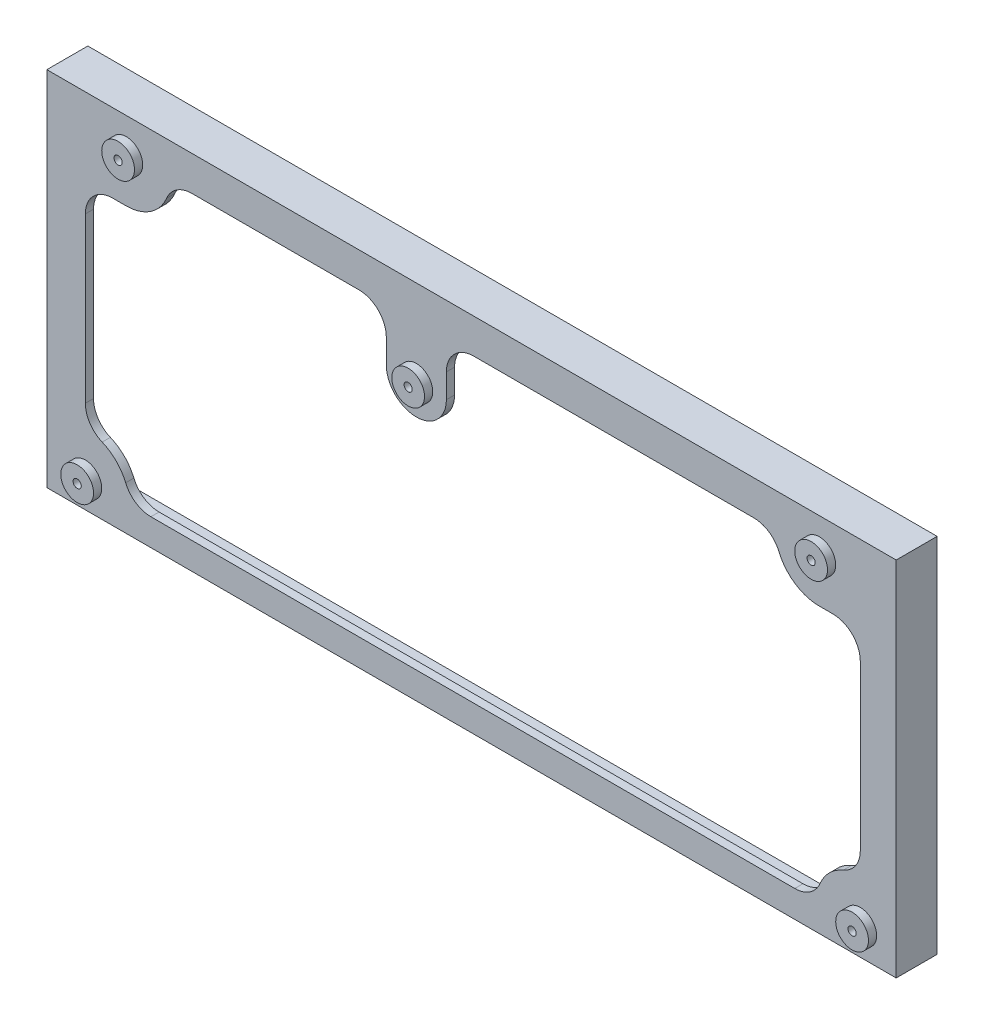
SolidWorks part; units mm, degrees
ref_plane "Front Plane" through (0, 0, 0) normal (0, 0, 1) x (1, 0, 0)
ref_plane "Top Plane" through (0, 0, 0) normal (0, 1, 0) x (1, 0, 0)
ref_plane "Right Plane" through (0, 0, 0) normal (1, 0, 0) x (0, 0, -1)
sketch "Sketch1" plane through (0, 0, 0) normal (0, 0, 1) x (1, 0, 0)
  circle A0 centre (0, 0) radius 1.5
  circle A1 centre (-106.24, 18.83) radius 1.5
  circle A2 centre (147.61, 18.83) radius 1.5
  circle A3 centre (-121.24, -91.25) radius 1.5
  circle A4 centre (162.61, -91.25) radius 1.5
  circle A5 centre (0, 0) radius 6
  circle A6 centre (-106.24, 18.83) radius 6
  circle A7 centre (147.61, 18.83) radius 6
  circle A8 centre (-121.24, -91.25) radius 6
  circle A9 centre (162.61, -91.25) radius 6
  dimension "D1" = 3
  dimension "D4" = 18.83
  dimension "D5" = 162.61
  dimension "D2" = 147.61
  dimension "D3" = 106.24
  dimension "D6" = 121.24
  dimension "D7" = 91.25
  dimension "D8" = 4.5
extrude "Display screw pattern" add sketch "Sketch1" along normal blind 3
sketch "Sketch2" plane through (0, 0, 0) normal (0, 0, -1) x (-1, 0, 0)
  line L0 (135.34, 31.53) -> (135.34, -101.07)
  line L1 (133.84, 30.03) -> (-174.26, 30.03) construction
  line L2 (133.84, 30.03) -> (133.84, -99.57) construction
  line L3 (133.84, -99.57) -> (-174.26, -99.57) construction
  line L4 (-174.26, 30.03) -> (-174.26, -99.57) construction
  line L5 (135.34, -101.07) -> (-175.76, -101.07)
  line L6 (-175.76, 31.53) -> (-175.76, -101.07)
  line L7 (135.34, 31.53) -> (-175.76, 31.53)
  circle A2 centre (106.24, 18.83) radius 4
  circle A3 centre (106.24, 18.83) radius 4
  circle A8 centre (0, 0) radius 4
  circle A9 centre (0, 0) radius 4
  circle A11 centre (121.24, -91.25) radius 4
  circle A12 centre (121.24, -91.25) radius 4
  circle A14 centre (-147.61, 18.83) radius 4
  circle A15 centre (-147.61, 18.83) radius 4
  circle A17 centre (-162.61, -91.25) radius 4
  circle A18 centre (-162.61, -91.25) radius 4
  dimension "D6" = 11.2
  dimension "D7" = 26.65
  dimension "D8" = 8.32
  dimension "D9" = 27.6
  dimension "D1" = 2
  dimension "D2" = 2
  dimension "D3" = 2
  dimension "D4" = 2
  dimension "D5" = 2
  dimension "D10" = 1.5
extrude "Display backplane" add sketch "Sketch2" along normal blind 3
sketch "Sketch3" plane through (0, 0, 0) normal (0, 0, 1) x (1, 0, 0)
  line L1 (162.61, -7.17) -> (162.61, -67.25)
  line L2 (138.61, -91.25) -> (-97.24, -91.25)
  line L3 (-121.24, -67.25) -> (-121.24, -7.17)
  line L5 (-82.24, 18.83) -> (-21, 18.83)
  line L6 (11, 8.83) -> (11, 0)
  line L7 (-11, 0) -> (-11, 8.83)
  line L8 (21, 18.83) -> (123.61, 18.83)
  line L9 (147.61, 2.83) -> (152.61, 2.83)
  line L10 (-106.24, 2.83) -> (-111.24, 2.83)
  arc A0 (123.61, 18.83) -> (132.8408, 12.6762) centre (123.61, 8.83) cw
  arc A1 (152.61, 2.83) -> (162.61, -7.17) centre (152.61, -7.17) cw
  arc A2 (162.61, -67.25) -> (156.4562, -76.4808) centre (152.61, -67.25) cw
  circle A4 centre (-121.24, -91.25) radius 16
  arc A5 (-106.4708, -85.0962) -> (-115.0862, -76.4808) centre (-121.24, -91.25) ccw
  arc A6 (138.61, -91.25) -> (147.8408, -85.0962) centre (138.61, -81.25) ccw
  circle A7 centre (162.61, -91.25) radius 16
  arc A8 (156.4562, -76.4808) -> (147.8408, -85.0962) centre (162.61, -91.25) ccw
  arc A9 (-97.24, -91.25) -> (-106.4708, -85.0962) centre (-97.24, -81.25) cw
  arc A10 (-121.24, -67.25) -> (-115.0862, -76.4808) centre (-111.24, -67.25) ccw
  arc A11 (-111.24, 2.83) -> (-121.24, -7.17) centre (-111.24, -7.17) ccw
  arc A12 (-82.24, 18.83) -> (-91.4708, 12.6762) centre (-82.24, 8.83) ccw
  circle A15 centre (0, 0) radius 11
  arc A16 (-11, 0) -> (11, 0) centre (0, 0) ccw
  arc A29 (21, 18.83) -> (11, 8.83) centre (21, 8.83) ccw
  arc A30 (-11, 8.83) -> (-21, 18.83) centre (-21, 8.83) ccw
  circle A36 centre (-106.24, 18.83) radius 16
  arc A37 (-106.24, 2.83) -> (-91.4708, 12.6762) centre (-106.24, 18.83) ccw
  circle A38 centre (147.61, 18.83) radius 16
  arc A39 (132.8408, 12.6762) -> (147.61, 2.83) centre (147.61, 18.83) ccw
  point P29 (131.61, 18.83)
  point P43 (162.61, -75.25)
  point P47 (146.61, -91.25)
  point P50 (-105.24, -91.25)
  point P53 (-121.24, -75.25)
  point P58 (-90.24, 18.83)
  dimension "D6" = 10
  dimension "D7" = 10
  dimension "D1" = 10
  dimension "D2" = 5
  dimension "D3" = 10
  dimension "D4" = 10
  dimension "D5" = 10
extrude "Backplane weight reduction" cut sketch "Sketch3" against normal through all both and the other way through all
sketch "Sketch4" plane through (0, 0, -3) normal (0, 0, -1) x (-1, 0, 0)
  line L12 (134.34, 30.53) -> (-174.76, 30.53)
  line L13 (-174.76, 30.53) -> (-174.76, -100.07)
  line L14 (-174.76, -100.07) -> (134.34, -100.07)
  line L15 (134.34, -100.07) -> (134.34, 30.53)
  line L16 (135.34, 31.53) -> (-175.76, 31.53)
  line L17 (-175.76, 31.53) -> (-175.76, -101.07)
  line L18 (-175.76, -101.07) -> (135.34, -101.07)
  line L19 (135.34, -101.07) -> (135.34, 31.53)
  line L20 (135.34, 31.53) -> (-175.76, 31.53)
  line L21 (-175.76, 31.53) -> (-175.76, -101.07)
  line L22 (-175.76, -101.07) -> (135.34, -101.07)
  line L23 (135.34, -101.07) -> (135.34, 31.53)
  dimension "D1" = 0
  dimension "D2" = 1
extrude "Display outside craddle" add sketch "Sketch4" along normal blind 12
